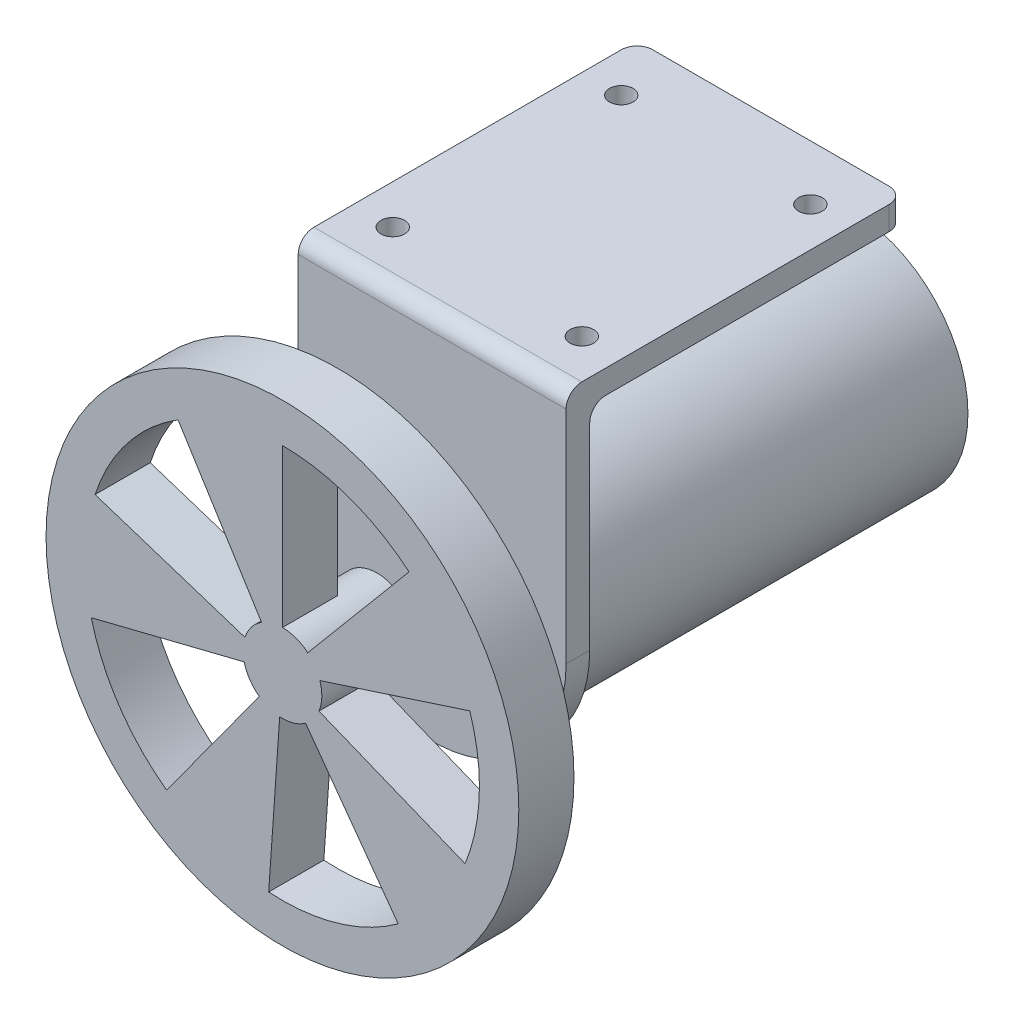
SolidWorks part; units mm, degrees
ref_plane "Front Plane" through (0, 0, 0) normal (0, 0, 1) x (1, 0, 0)
ref_plane "Top Plane" through (0, 0, 0) normal (0, 1, 0) x (1, 0, 0)
ref_plane "Right Plane" through (0, 0, 0) normal (1, 0, 0) x (0, 0, -1)
sketch "Sketch1" plane through (0, 0, 0) normal (0, 0, 1) x (1, 0, 0)
  circle A0 centre (0, 0) radius 15
  dimension "D1" = 30
extrude "Boss-Extrude1" add sketch "Sketch1" along normal blind 50
sketch "Sketch2" plane through (0, 0, 50) normal (0, 0, 1) x (1, 0, 0)
  circle A0 centre (0, 0) radius 1.5
  dimension "D1" = 3
extrude "Boss-Extrude2" add sketch "Sketch2" along normal blind 15
sketch "Sketch4" plane through (0, 0, 50) normal (0, 0, 1) x (1, 0, 0)
  line L0 (-17, 0) -> (-17, 30)
  line L1 (-17, 30) -> (17, 30)
  line L2 (17, 30) -> (17, 0)
  arc A0 (17, 0) -> (-17, 0) centre (0, 0) cw
  dimension "D1" = 17
  dimension "D2" = 30
extrude "Boss-Extrude4" add sketch "Sketch4" along normal blind 3
sketch "Sketch5" plane through (0, 0, 50) normal (0, 0, -1) x (-1, 0, 0)
  line L0 (17, 30) -> (17, 0) construction
  line L1 (-17, 30) -> (17, 30)
  line L2 (-17, 30) -> (-17, 27)
  line L3 (-17, 27) -> (17, 27)
  line L4 (17, 30) -> (17, 27)
  dimension "D1" = 3
extrude "Boss-Extrude5" add sketch "Sketch5" along normal blind 40
fillet "Fillet2" radius 2 4 edges at (-17, 28.5, 10) (17, 28.5, 10) (0, 27, 50) (0, 30, 53)
sketch "Sketch6" plane through (0, 0, 65) normal (0, 0, 1) x (1, 0, 0)
  circle A0 centre (0, 0) radius 30
  dimension "D1" = 60
extrude "Boss-Extrude6" add sketch "Sketch6" along normal blind 7
sketch "Sketch7" plane through (0, 0, 72) normal (0, 0, 1) x (1, 0, 0)
  line L0 (0, 25) -> (0, 5)
  line L1 (3.2139, 3.8302) -> (16.0697, 19.1511)
  line L2 (23.7764, 7.7254) -> (4.7553, 1.5451)
  line L3 (4.6359, -1.873) -> (23.1796, -9.3652)
  line L4 (14.6946, -20.2254) -> (2.9389, -4.0451)
  line L5 (-0.3488, -4.9878) -> (-1.7439, -24.9391)
  line L6 (-14.6946, -20.2254) -> (-2.9389, -4.0451)
  line L7 (-4.8515, -1.2096) -> (-24.2574, -6.048)
  line L8 (-23.7764, 7.7254) -> (-4.7553, 1.5451)
  line L9 (-2.6496, 4.2402) -> (-13.248, 21.2012)
  arc A0 (0, 25) -> (16.0697, 19.1511) centre (0, 0) cw
  arc A1 (0, 5) -> (3.2139, 3.8302) centre (0, 0) cw
  arc A2 (23.7764, 7.7254) -> (23.1796, -9.3652) centre (0, 0) cw
  arc A3 (4.7553, 1.5451) -> (4.6359, -1.873) centre (0, 0) cw
  arc A4 (14.6946, -20.2254) -> (-1.7439, -24.9391) centre (0, 0) cw
  arc A5 (2.9389, -4.0451) -> (-0.3488, -4.9878) centre (0, 0) cw
  arc A6 (-14.6946, -20.2254) -> (-24.2574, -6.048) centre (0, 0) cw
  arc A7 (-2.9389, -4.0451) -> (-4.8515, -1.2096) centre (0, 0) cw
  arc A8 (-23.7764, 7.7254) -> (-13.248, 21.2012) centre (0, 0) cw
  arc A9 (-4.7553, 1.5451) -> (-2.6496, 4.2402) centre (0, 0) cw
  point P24 (0, 0)
  dimension "D1" = 25
  dimension "D4" = 5
  dimension "D2" = 25
  dimension "D3" = 25
  dimension "D5" = 40
  dimension "D6" = 20
  dimension "D7" = 20
  dimension "D8" = 5
extrude "Cut-Extrude1" cut sketch "Sketch7" against normal blind 7
sketch "Sketch8" plane through (0, 0, 65) normal (0, 0, -1) x (-1, 0, 0)
  circle A0 centre (0, 0) radius 5
  dimension "D1" = 10
extrude "Boss-Extrude7" add sketch "Sketch8" along normal blind 5
sketch "Sketch9" plane through (0, 30, 0) normal (0, 1, 0) x (1, 0, 0)
  line L0 (-17, -51) -> (-17, -12) construction
  line L1 (-17, -51) -> (17, -51) construction
  line L2 (0, -10) -> (0, -51) construction
  line L3 (-15, -10) -> (15, -10) construction
  line L4 (17, -31.5) -> (-17, -31.5) construction
  line L5 (17, -51) -> (17, -12) construction
  circle A0 centre (-12, -46) radius 1.5
  circle A1 centre (-12, -17) radius 1.5
  circle A2 centre (12, -46) radius 1.5
  circle A3 centre (12, -17) radius 1.5
  dimension "D1" = 3
  dimension "D2" = 5
  dimension "D3" = 5
  dimension "D4" = 19.5
extrude "Cut-Extrude2" cut sketch "Sketch9" against normal blind 5
